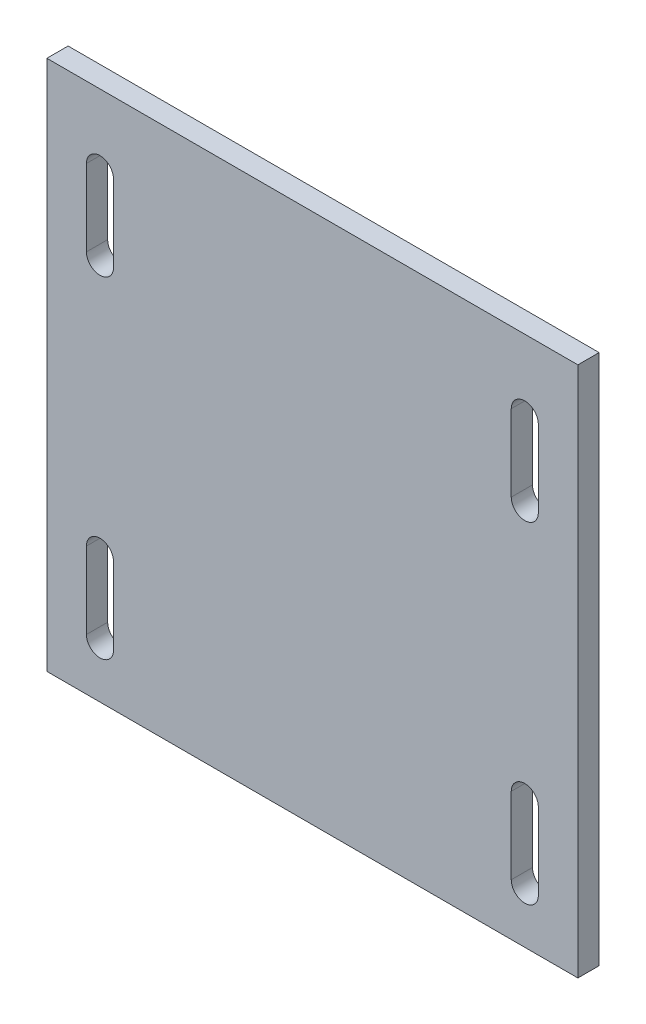
SolidWorks part; units mm, degrees
ref_plane "Front Plane" through (0, 0, 0) normal (0, 0, 1) x (1, 0, 0)
ref_plane "Top Plane" through (0, 0, 0) normal (0, 1, 0) x (1, 0, 0)
ref_plane "Right Plane" through (0, 0, 0) normal (1, 0, 0) x (0, 0, -1)
sketch "Sketch1" plane through (0, 0, 0) normal (0, 0, 1) x (1, 0, 0)
  line L2 (0, 0) -> (0, 90)
  line L3 (0, 90) -> (100, 90)
  line L4 (100, 2.3723) -> (100, 90)
  line L7 (10, 14.1724) -> (10, -0.2503) construction
  line L10 (90, 14.1724) -> (90, -0.2503) construction
  line L13 (7.45, 14.1724) -> (7.45, -0.2503)
  line L16 (0, 0) -> (0, -10)
  line L17 (0, -10) -> (100, -10)
  line L18 (100, -10) -> (100, 2.3723)
  line L20 (90, 62.1506) -> (90, 76.5733) construction
  line L21 (87.45, 62.1506) -> (87.45, 76.5733)
  line L22 (92.55, 62.1506) -> (92.55, 76.5733)
  line L23 (92.55, 14.1724) -> (92.55, -0.2503)
  line L24 (87.45, 14.1724) -> (87.45, -0.2503)
  line L25 (12.55, 14.1724) -> (12.55, -0.2503)
  line L26 (10, 62.1506) -> (10, 76.5733) construction
  line L27 (12.55, 62.1506) -> (12.55, 76.5733)
  line L28 (7.45, 62.1506) -> (7.45, 76.5733)
  arc A13 (87.45, 62.1506) -> (92.55, 62.1506) centre (90, 62.1506) ccw
  arc A14 (92.55, 76.5733) -> (87.45, 76.5733) centre (90, 76.5733) ccw
  arc A15 (92.55, 14.1724) -> (87.45, 14.1724) centre (90, 14.1724) ccw
  arc A16 (87.45, -0.2503) -> (92.55, -0.2503) centre (90, -0.2503) ccw
  arc A17 (7.45, 14.1724) -> (12.55, 14.1724) centre (10, 14.1724) cw
  arc A18 (12.55, -0.2503) -> (7.45, -0.2503) centre (10, -0.2503) cw
  arc A19 (12.55, 62.1506) -> (7.45, 62.1506) centre (10, 62.1506) cw
  arc A20 (7.45, 76.5733) -> (12.55, 76.5733) centre (10, 76.5733) cw
  point P8 (10, 6.9611)
  point P15 (10, 69.3619)
  point P21 (90, 6.9611)
  point P33 (50, 40)
  point P48 (90, 69.3619)
  dimension "D5" = 13.4267
  dimension "D6" = 9.7497
  dimension "D9" = 2.55
  dimension "D8" = 2.55
  dimension "D2" = 100
  dimension "D3" = 50
  dimension "D4" = 10
  dimension "D7" = 100
  dimension "D11" = 14.4227
  dimension "D12" = 10
extrude "Boss-Extrude1" add sketch "Sketch1" along normal blind 4
